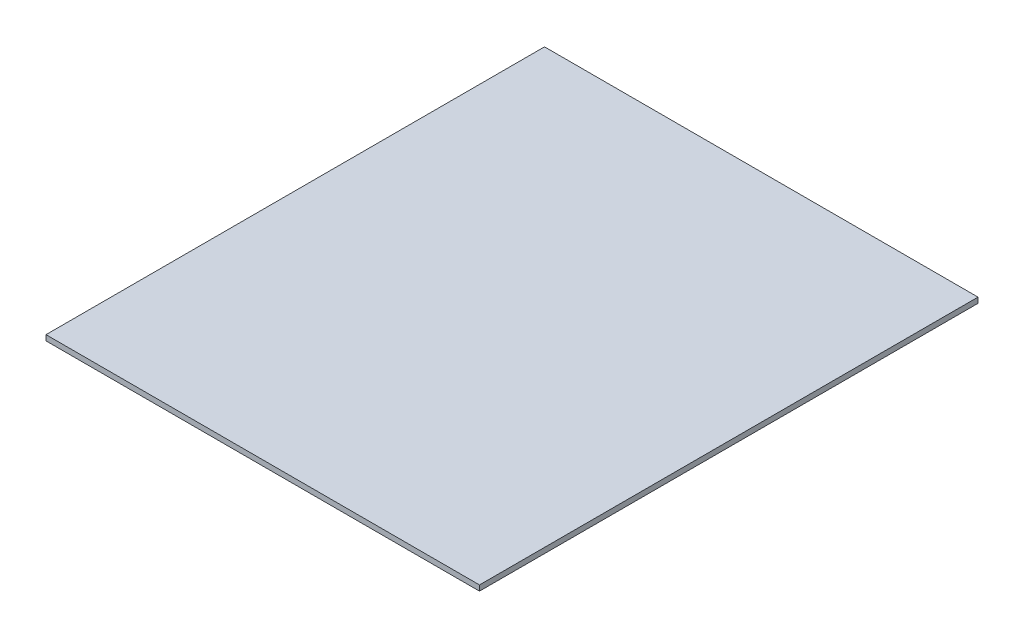
SolidWorks part; units mm, degrees
ref_plane "Front Plane" through (0, 0, 0) normal (0, 0, 1) x (1, 0, 0)
ref_plane "Top Plane" through (0, 0, 0) normal (0, 1, 0) x (1, 0, 0)
ref_plane "Right Plane" through (0, 0, 0) normal (1, 0, 0) x (0, 0, -1)
sketch "Sketch1" plane through (0, 0, 0) normal (0, 1, 0) x (1, 0, 0)
  line L1 (0, 0) -> (254, 0)
  line L2 (0, 0) -> (0, 292.1)
  line L3 (0, 292.1) -> (254, 292.1)
  line L4 (254, 0) -> (254, 292.1)
  dimension "D1" = 292.1
  dimension "D2" = 254
extrude "Boss-Extrude1" add sketch "Sketch1" along normal blind 3.175
